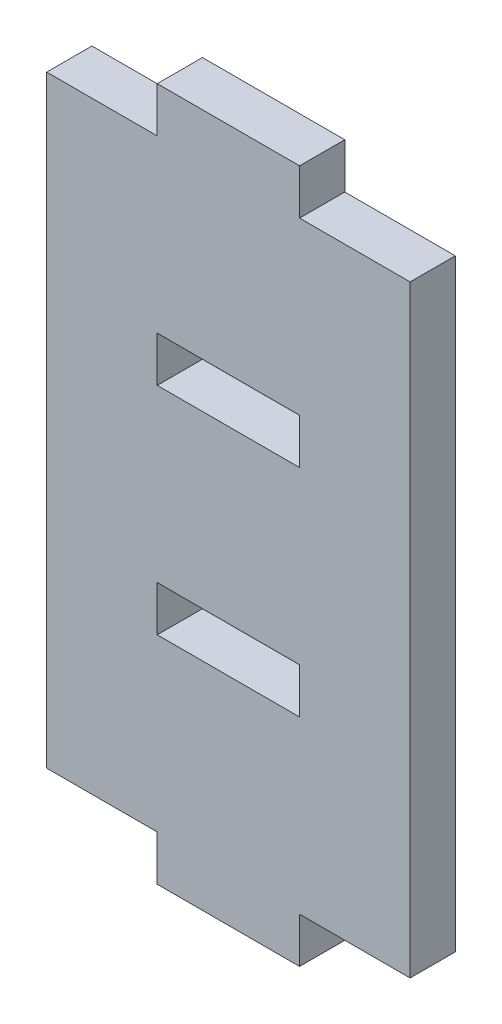
SolidWorks part; units mm, degrees
ref_plane "Front Plane" through (0, 0, 0) normal (0, 0, 1) x (1, 0, 0)
ref_plane "Top Plane" through (0, 0, 0) normal (0, 1, 0) x (1, 0, 0)
ref_plane "Right Plane" through (0, 0, 0) normal (1, 0, 0) x (0, 0, -1)
sketch "Sketch1" plane through (0, 0, 0) normal (0, 0, 1) x (1, 0, 0)
  line L0 (0, 0) -> (0, -3.18)
  line L1 (0, -3.18) -> (-10, -3.18)
  line L2 (-10, -3.18) -> (-10, 0)
  line L3 (-10, 0) -> (-17.765, 0)
  line L4 (-17.765, 0) -> (-17.765, 42.35)
  line L5 (-17.765, 42.35) -> (-10, 42.35)
  line L6 (-10, 42.35) -> (-10, 45.53)
  line L7 (-10, 45.53) -> (0, 45.53)
  line L8 (0, 45.53) -> (0, 42.35)
  line L9 (0, 42.35) -> (7.765, 42.35)
  line L10 (7.765, 42.35) -> (7.765, 0)
  line L11 (7.765, 0) -> (0, 0)
  line L12 (0, 11.9967) -> (-10, 11.9967)
  line L13 (-10, 11.9967) -> (-10, 15.1767)
  line L14 (-10, 15.1767) -> (0, 15.1767)
  line L15 (0, 15.1767) -> (0, 11.9967)
  line L16 (0, 27.1733) -> (-10, 27.1733)
  line L17 (-10, 27.1733) -> (-10, 30.3533)
  line L18 (-10, 30.3533) -> (0, 30.3533)
  line L19 (0, 30.3533) -> (0, 27.1733)
  line L20 (-5, -3.18) -> (-5, 99.437) construction
  line L21 (0, 11.9967) -> (0, 0) construction
  line L22 (0, 15.1767) -> (0, 27.1733) construction
  line L23 (0, 30.3533) -> (0, 42.35) construction
  point P19 (-5, 15.1767)
  point P22 (-5, -3.18)
  point P24 (-5, 30.3533)
  dimension "D1" = 10
  dimension "D2" = 3.18
  dimension "D3" = 25.53
  dimension "D4" = 11.9967
extrude "Boss-Extrude1" add sketch "Sketch1" along normal mid plane 3.175
